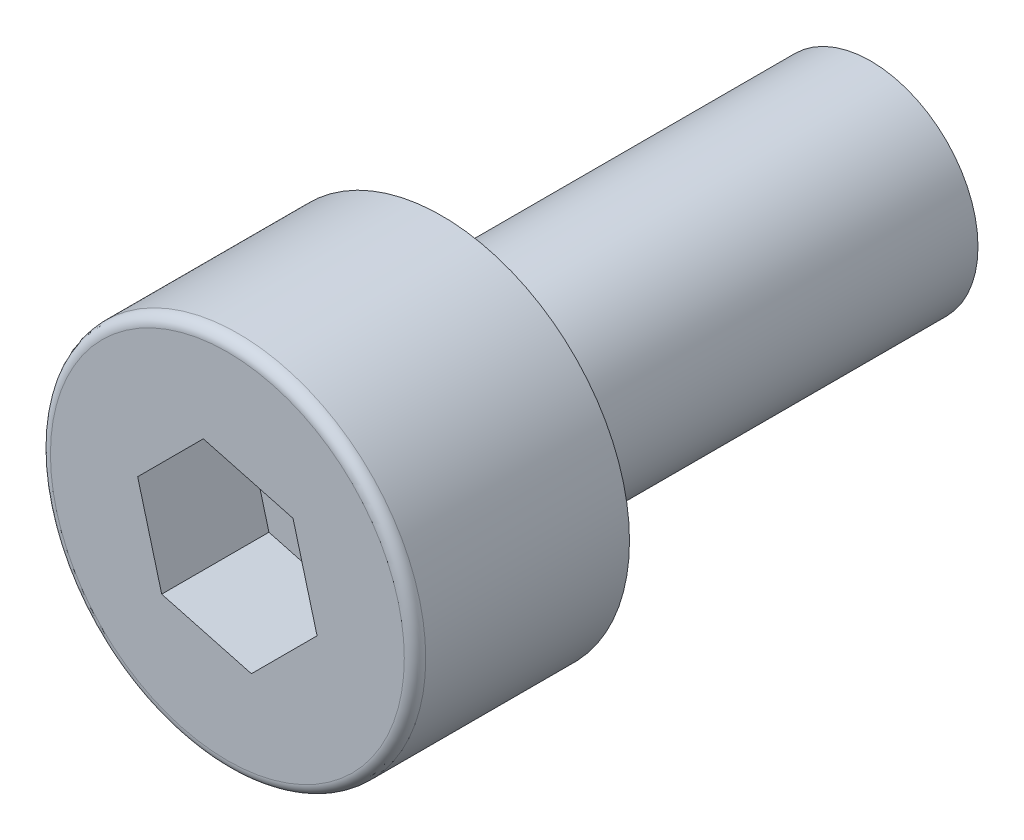
SolidWorks part; units mm, degrees
ref_plane "前视基准面" through (0, 0, 0) normal (0, 0, 1) x (1, 0, 0)
ref_plane "上视基准面" through (0, 0, 0) normal (0, 1, 0) x (1, 0, 0)
ref_plane "右视基准面" through (0, 0, 0) normal (1, 0, 0) x (0, 0, -1)
sketch "草图1" plane through (0, 0, 0) normal (0, 0, 1) x (1, 0, 0)
  circle A0 centre (0, 0) radius 3.5
  dimension "D1" = 7
extrude "凸台-拉伸1" add sketch "草图1" along normal blind 4
sketch "草图2" plane through (0, 0, 4) normal (0, 0, 1) x (1, 0, 0)
  line L1 (-1.2247, -1.2247) -> (0.4483, -1.673)
  line L2 (0.4483, -1.673) -> (1.673, -0.4483)
  line L3 (1.673, -0.4483) -> (1.2247, 1.2247)
  line L4 (1.2247, 1.2247) -> (-0.4483, 1.673)
  line L5 (-0.4483, 1.673) -> (-1.673, 0.4483)
  line L6 (-1.673, 0.4483) -> (-1.2247, -1.2247)
  circle A0 centre (0, 0) radius 1.5 construction
  dimension "D1" = 3
extrude "切除-拉伸1" cut sketch "草图2" against normal blind 2
sketch "草图3" plane through (0, 0, 0) normal (0, 0, -1) x (-1, 0, 0)
  circle A0 centre (0, 0) radius 2
  dimension "D1" = 4
extrude "凸台-拉伸2" add sketch "草图3" along normal blind 8
fillet "圆角1" radius 0.2 1 edges at (3.5, 0, 4)
